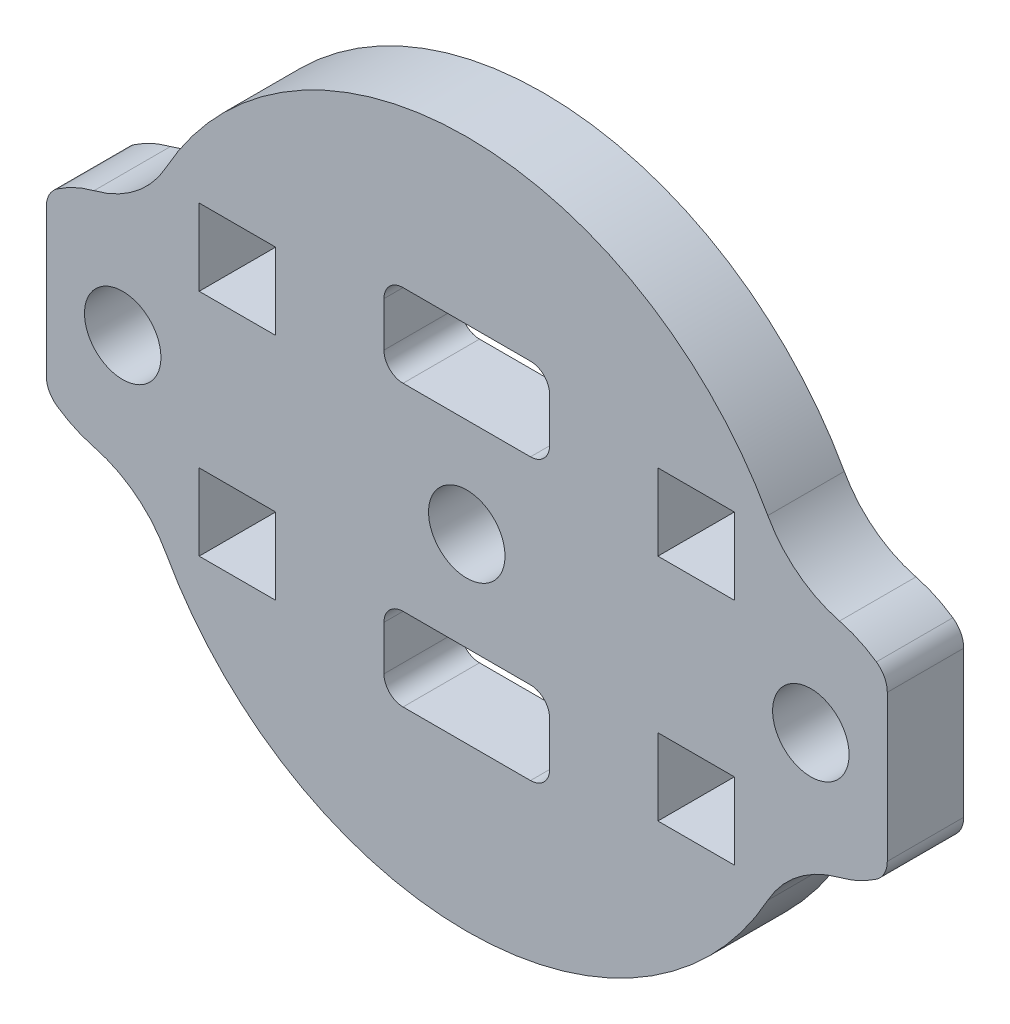
SolidWorks part; units mm, degrees
ref_plane "Alzado" through (0, 0, 0) normal (0, 0, 1) x (1, 0, 0)
ref_plane "Planta" through (0, 0, 0) normal (0, 1, 0) x (1, 0, 0)
ref_plane "Vista lateral" through (0, 0, 0) normal (1, 0, 0) x (0, 0, -1)
sketch "Model" plane through (0, 0, 0) normal (0, 0, 1) x (1, 0, 0)
  line L0 (34.9937, 286.7661) -> (37.9937, 286.7661)
  line L1 (34.9937, 289.7661) -> (34.9937, 286.7661)
  line L2 (37.9937, 289.7661) -> (34.9937, 289.7661)
  line L3 (37.9937, 286.7661) -> (37.9937, 289.7661)
  line L4 (34.9937, 277.7661) -> (37.9937, 277.7661)
  line L5 (34.9937, 280.7661) -> (34.9937, 277.7661)
  line L6 (37.9937, 280.7661) -> (34.9937, 280.7661)
  line L7 (37.9937, 277.7661) -> (37.9937, 280.7661)
  line L8 (16.9937, 286.7661) -> (19.9937, 286.7661)
  line L9 (16.9937, 289.7661) -> (16.9937, 286.7661)
  line L10 (19.9937, 289.7661) -> (16.9937, 289.7661)
  line L11 (19.9937, 286.7661) -> (19.9937, 289.7661)
  line L12 (16.9937, 277.7661) -> (19.9937, 277.7661)
  line L13 (16.9937, 280.7661) -> (16.9937, 277.7661)
  line L14 (19.9937, 280.7661) -> (16.9937, 280.7661)
  line L15 (19.9937, 277.7661) -> (19.9937, 280.7661)
  line L16 (30.7437, 277.3911) -> (30.7437, 279.1411)
  line L17 (24.9937, 276.6411) -> (29.9937, 276.6411)
  line L18 (24.2437, 279.1411) -> (24.2437, 277.3911)
  line L19 (29.9937, 279.8911) -> (24.9937, 279.8911)
  line L20 (30.7437, 290.1411) -> (30.7437, 288.3911)
  line L21 (24.9937, 290.8911) -> (29.9937, 290.8911)
  line L22 (24.2437, 288.3911) -> (24.2437, 290.1411)
  line L23 (29.9937, 287.6411) -> (24.9937, 287.6411)
  line L24 (10.9937, 286.6384) -> (10.9937, 280.8938)
  line L25 (43.9937, 286.6384) -> (43.9937, 280.8938)
  arc A0 (42.1187, 279.409) -> (39.3062, 277.2304) centre (43.2437, 275.0519) ccw
  arc A1 (39.3062, 290.3017) -> (42.1187, 288.1232) centre (43.2437, 292.4803) ccw
  arc A2 (15.6812, 277.2304) -> (12.8687, 279.409) centre (11.7437, 275.0519) ccw
  arc A3 (12.8687, 288.1232) -> (15.6812, 290.3017) centre (11.7437, 292.4803) ccw
  arc A4 (12.8687, 288.1232) -> (11.4222, 287.459) centre (13.9937, 283.7661) ccw
  circle A5 centre (40.9937, 283.7661) radius 1.5
  circle A6 centre (13.9937, 283.7661) radius 1.5
  circle A7 centre (27.4937, 283.7661) radius 1.5
  arc A8 (30.7437, 279.1411) -> (29.9937, 279.8911) centre (29.9937, 279.1411) ccw
  arc A9 (29.9937, 276.6411) -> (30.7437, 277.3911) centre (29.9937, 277.3911) ccw
  arc A10 (24.2437, 277.3911) -> (24.9937, 276.6411) centre (24.9937, 277.3911) ccw
  arc A11 (24.9937, 279.8911) -> (24.2437, 279.1411) centre (24.9937, 279.1411) ccw
  arc A12 (29.9937, 287.6411) -> (30.7437, 288.3911) centre (29.9937, 288.3911) ccw
  arc A13 (30.7437, 290.1411) -> (29.9937, 290.8911) centre (29.9937, 290.1411) ccw
  arc A14 (24.9937, 290.8911) -> (24.2437, 290.1411) centre (24.9937, 290.1411) ccw
  arc A15 (24.2437, 288.3911) -> (24.9937, 287.6411) centre (24.9937, 288.3911) ccw
  arc A16 (42.1187, 279.409) -> (43.5651, 280.0731) centre (40.9937, 283.7661) ccw
  arc A17 (39.3062, 290.3017) -> (15.6812, 290.3017) centre (27.4937, 283.7661) ccw
  arc A18 (15.6812, 277.2304) -> (39.3062, 277.2304) centre (27.4937, 283.7661) ccw
  arc A19 (11.4222, 280.0731) -> (12.8687, 279.409) centre (13.9937, 283.7661) ccw
  arc A20 (43.5651, 287.459) -> (42.1187, 288.1232) centre (40.9937, 283.7661) ccw
  arc A21 (11.4222, 287.459) -> (10.9937, 286.6384) centre (11.9937, 286.6384) ccw
  arc A22 (10.9937, 280.8938) -> (11.4222, 280.0731) centre (11.9937, 280.8938) ccw
  arc A23 (43.5651, 280.0731) -> (43.9937, 280.8938) centre (42.9937, 280.8938) ccw
  arc A24 (43.9937, 286.6384) -> (43.5651, 287.459) centre (42.9937, 286.6384) ccw
extrude "Saliente-Extruir1" add sketch "Model" along normal blind 3
